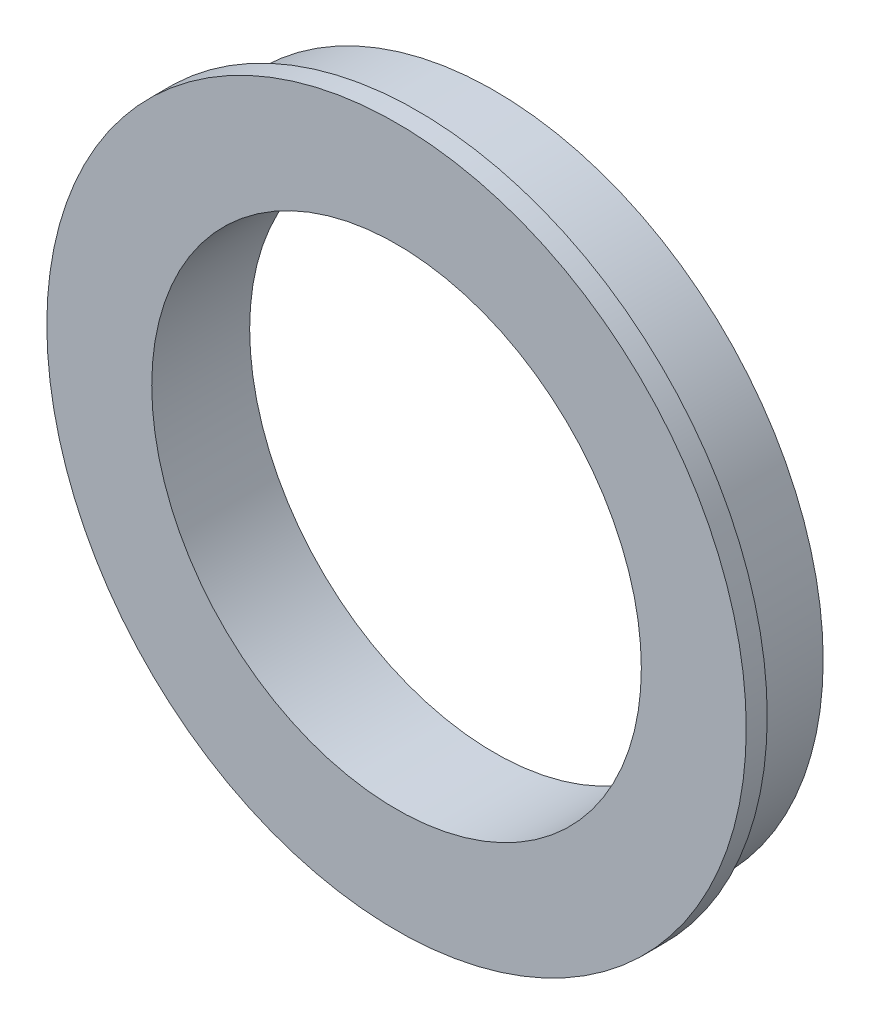
SolidWorks part; units mm, degrees
ref_plane "前视基准面" through (0, 0, 0) normal (0, 0, 1) x (1, 0, 0)
ref_plane "上视基准面" through (0, 0, 0) normal (0, 1, 0) x (1, 0, 0)
ref_plane "右视基准面" through (0, 0, 0) normal (1, 0, 0) x (0, 0, -1)
other "Configuration Table"
sketch "草图1" plane through (0, 0, 0) normal (0, 0, 1) x (1, 0, 0)
  circle A0 centre (0, 0) radius 17.5
  circle A1 centre (0, 0) radius 23.5
  dimension "D1" = 35
  dimension "D2" = 47
extrude "凸台-拉伸1" add sketch "草图1" along normal blind 5.5
sketch "草图2" plane through (0, 0, 5.5) normal (0, 0, 1) x (1, 0, 0)
  circle A0 centre (0, 0) radius 25
  circle A2 centre (0, 0) radius 17.5
  dimension "D1" = 50
extrude "凸台-拉伸2" add sketch "草图2" along normal blind 1.5
